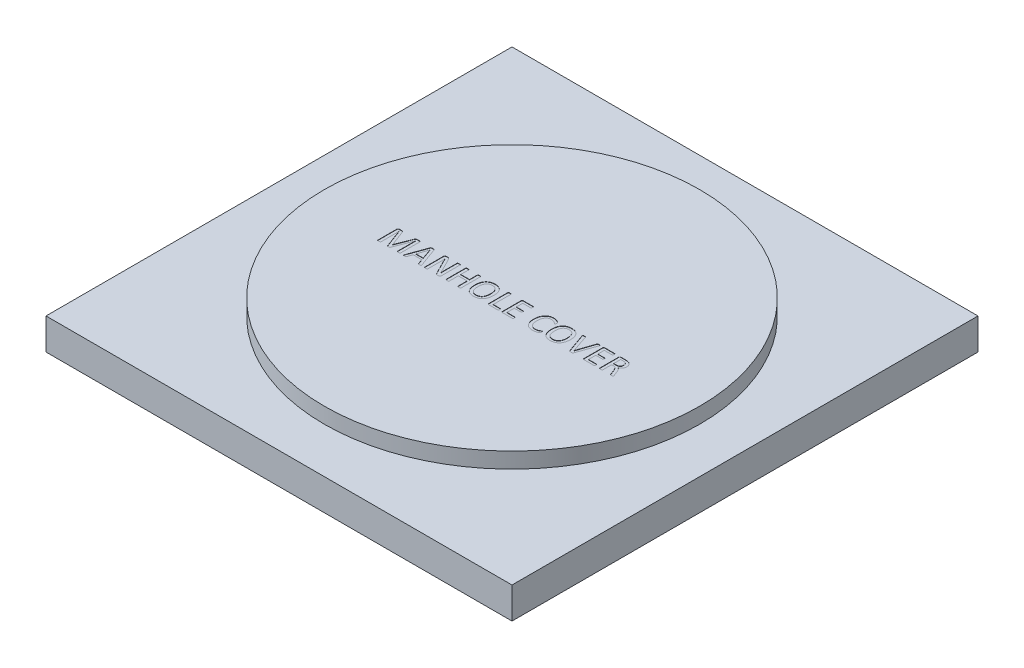
SolidWorks part; units mm, degrees
ref_plane "Front Plane" through (0, 0, 0) normal (0, 0, 1) x (1, 0, 0)
ref_plane "Top Plane" through (0, 0, 0) normal (0, 1, 0) x (1, 0, 0)
ref_plane "Right Plane" through (0, 0, 0) normal (1, 0, 0) x (0, 0, -1)
sketch "Sketch1" plane through (0, 0, 0) normal (0, 1, 0) x (1, 0, 0)
  line L1 (-745, 745) -> (745, 745)
  line L2 (-745, 745) -> (-745, -745)
  line L3 (-745, -745) -> (745, -745)
  line L4 (745, 745) -> (745, -745)
  line L5 (-745, 745) -> (745, -745) construction
  line L6 (-745, -745) -> (745, 745) construction
  point P0 (0, 0)
  dimension "D1" = 1490
  dimension "D2" = 1490
extrude "Boss-Extrude1" add sketch "Sketch1" along normal blind 100
sketch "Sketch2" plane through (0, 100, 0) normal (0, 1, 0) x (1, 0, 0)
  circle A0 centre (0, 0) radius 600
  dimension "D1" = 1200
extrude "Boss-Extrude2" add sketch "Sketch2" along normal blind 50
sketch "Sketch3" plane through (0, 150, 0) normal (0, 1, 0) x (1, 0, 0)
  line L0 (-597.3746, -56.0676) -> (597.3746, -56.0676) construction
  circle A0 centre (0, 0) radius 600 construction
  text T0 "MANHOLE COVER" font "Calibri" height in points 250
extrude "Cut-Extrude1" cut sketch "Sketch3" against normal blind 1
